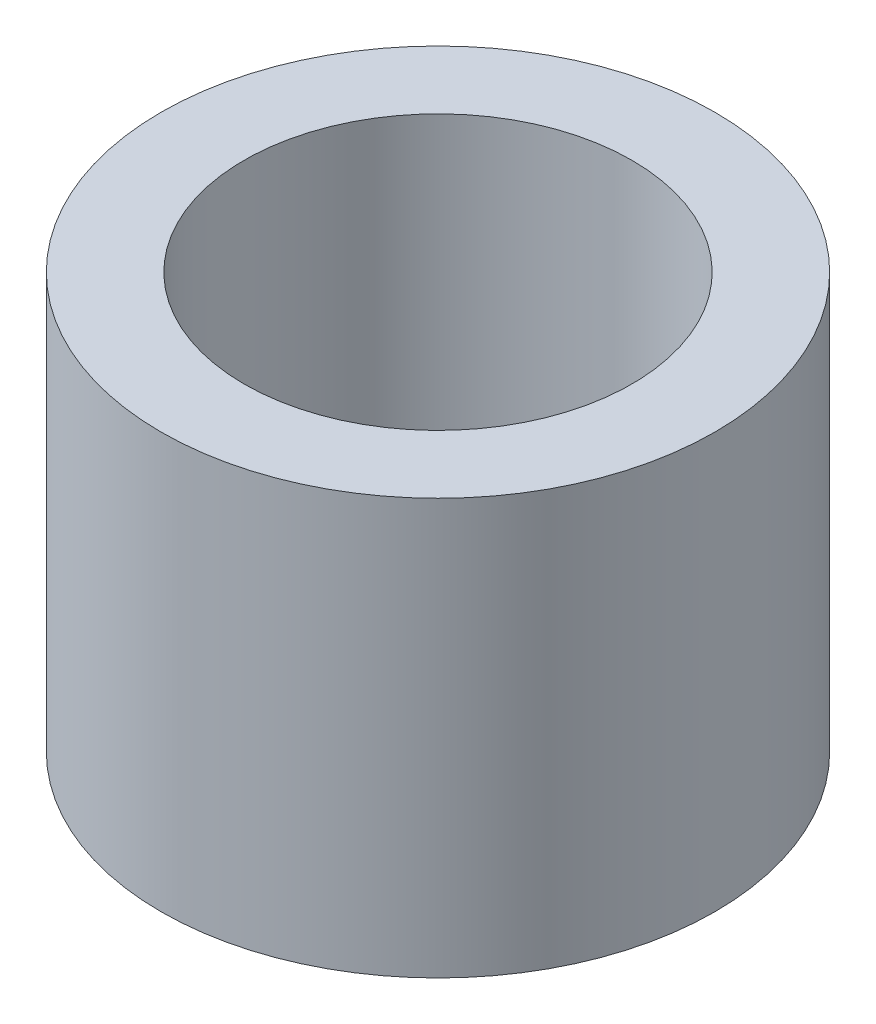
SolidWorks part; units mm, degrees
ref_plane "Front Plane" through (0, 0, 0) normal (0, 0, 1) x (1, 0, 0)
ref_plane "Top Plane" through (0, 0, 0) normal (0, 1, 0) x (1, 0, 0)
ref_plane "Right Plane" through (0, 0, 0) normal (1, 0, 0) x (0, 0, -1)
sketch "Sketch1" plane through (0, 0, 0) normal (0, 1, 0) x (1, 0, 0)
  circle A0 centre (0, 0) radius 7
  dimension "D1" = 14
extrude "Boss-Extrude1" add sketch "Sketch1" along normal blind 15
shell "Shell2" thickness 3
